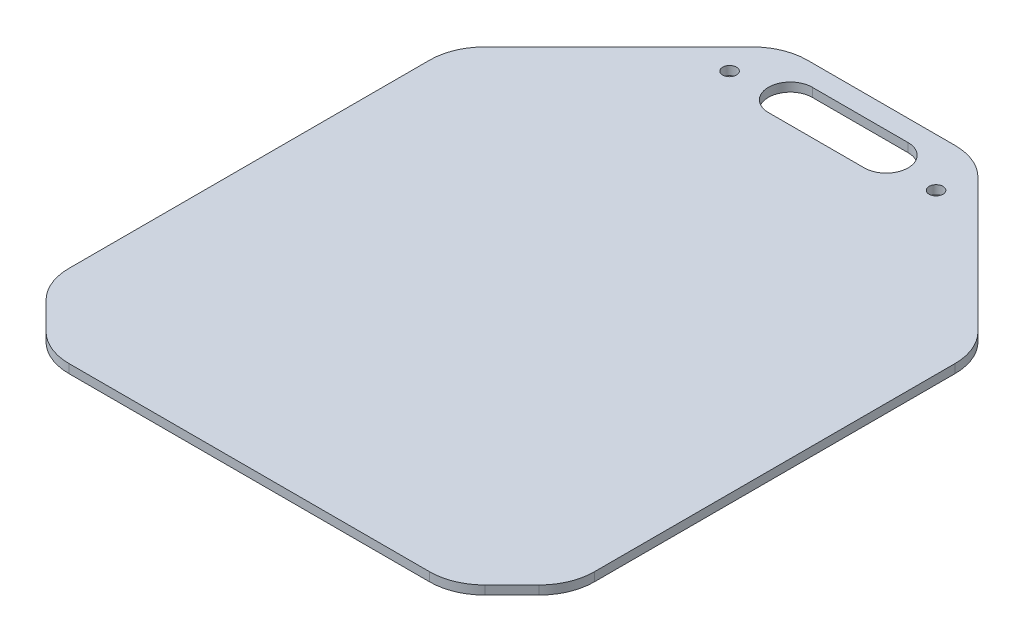
SolidWorks part; units mm, degrees
ref_plane "Front Plane" through (0, 0, 0) normal (0, 0, 1) x (1, 0, 0)
ref_plane "Top Plane" through (0, 0, 0) normal (0, 1, 0) x (1, 0, 0)
ref_plane "Right Plane" through (0, 0, 0) normal (1, 0, 0) x (0, 0, -1)
sketch "Sketch1" plane through (0, 0, 0) normal (0, 1, 0) x (1, 0, 0)
  line L0 (0, 0) -> (294, 0)
  line L1 (294, 0) -> (336.996, 43.004)
  line L2 (336.996, 43.004) -> (336.996, 337.004)
  line L3 (336.996, 337.004) -> (217, 457)
  line L4 (217, 457) -> (77, 457)
  line L5 (77, 457) -> (-42.996, 337.004)
  line L6 (-42.996, 337.004) -> (-42.996, 43.004)
  line L7 (-42.996, 43.004) -> (0, 0)
  dimension "D1" = 294
  dimension "D2" = 294
  dimension "D3" = 457
  dimension "D4" = 43.004
  dimension "D5" = 60.8112
  dimension "D6" = 42.996
  dimension "D7" = 169.7
  dimension "D8" = 119.996
  dimension "D9" = 225
  dimension "D10" = 140
  dimension "D11" = 119.996
extrude "Body" add sketch "Sketch1" along normal blind 6.35
sketch "Sketch2" plane through (0, 6.35, 0) normal (0, 1, 0) x (1, 0, 0)
  line L3 (217, 457) -> (77, 457) construction
  line L4 (112.35, 441.8) -> (181.65, 441.8)
  line L5 (112.35, 441.8) -> (112.35, 410.1)
  line L6 (112.35, 410.1) -> (181.65, 410.1)
  line L7 (181.65, 441.8) -> (181.65, 410.1)
  line L8 (217, 457) -> (77, 457)
  arc A1 (112.35, 441.8) -> (112.35, 410.1) centre (112.35, 425.95) ccw
  arc A2 (181.65, 441.8) -> (181.65, 410.1) centre (181.65, 425.95) cw
  point P8 (147, 410.1)
  point P9 (147, 457)
  dimension "D3" = 15.85
  dimension "D4" = 15.2
  dimension "D1" = 69.3
  dimension "D2" = 31.7
extrude "Handle" cut sketch "Sketch2" against normal blind 6.35 contours L6 A2 L4 A1
sketch "Sketch11" plane through (0, 6.35, 0) normal (0, 1, 0) x (1, 0, 0)
  line L0 (217, 457) -> (77, 457) construction
  circle A0 centre (221.65, 422) radius 5
  arc A1 (181.65, 410.1) -> (181.65, 441.8) centre (181.65, 425.95) ccw construction
  circle A2 centre (72.35, 422) radius 5
  arc A3 (112.35, 441.8) -> (112.35, 410.1) centre (112.35, 425.95) ccw construction
  dimension "D1" = 35
  dimension "D3" = 35
  dimension "D2" = 40
  dimension "D4" = 40
extrude "Locking Mechanism Holes" cut sketch "Sketch11" against normal blind 6.36 contours A0 | A2
fillet "Fillet1" radius 40 2 edges at (217, 3.175, -457) (77, 3.175, -457)
fillet "Fillet2" radius 40 6 edges at (-42.996, 3.175, -337.004) (-42.996, 3.175, -43.004) (0, 3.175, 0) (294, 3.175, 0) (336.996, 3.175, -43.004) (336.996, 3.175, -337.004)
sketch "Sketch12" plane through (0, 0, 0) normal (0, -1, 0) x (1, 0, 0)
  line L0 (147, -457) -> (147, -149.252) construction
  line L1 (200.4315, -457) -> (93.5685, -457) construction
  line L2 (297.6586, -192) -> (0, -192) construction
  line L3 (257.4, -267) -> (247.4, -267)
  line L4 (257.4, -267) -> (257.4, -237)
  line L5 (257.4, -237) -> (247.4, -237)
  line L6 (247.4, -267) -> (247.4, -237)
  line L7 (36.6, -117) -> (36.6, -147)
  line L8 (36.6, -237) -> (46.6, -237)
  line L9 (46.6, -267) -> (46.6, -237)
  line L10 (36.6, -267) -> (46.6, -267)
  line L11 (36.6, -267) -> (36.6, -237)
  line L12 (36.6, -117) -> (46.6, -117)
  line L13 (46.6, -117) -> (46.6, -147)
  line L14 (36.6, -147) -> (46.6, -147)
  line L15 (257.4, -147) -> (247.4, -147)
  line L16 (247.4, -117) -> (247.4, -147)
  line L17 (257.4, -117) -> (247.4, -117)
  line L18 (257.4, -117) -> (257.4, -147)
  dimension "D1" = 100.4
  dimension "D2" = 10
  dimension "D3" = 30
  dimension "D4" = 190
  dimension "D5" = 45
extrude "Boss-Extrude1" add sketch "Sketch12" along normal blind 4 contours L9 L8 L11 L10 | L4 L5 L6 L3 | L18 L15 L16 L17 | L13 L14 L7 L12
